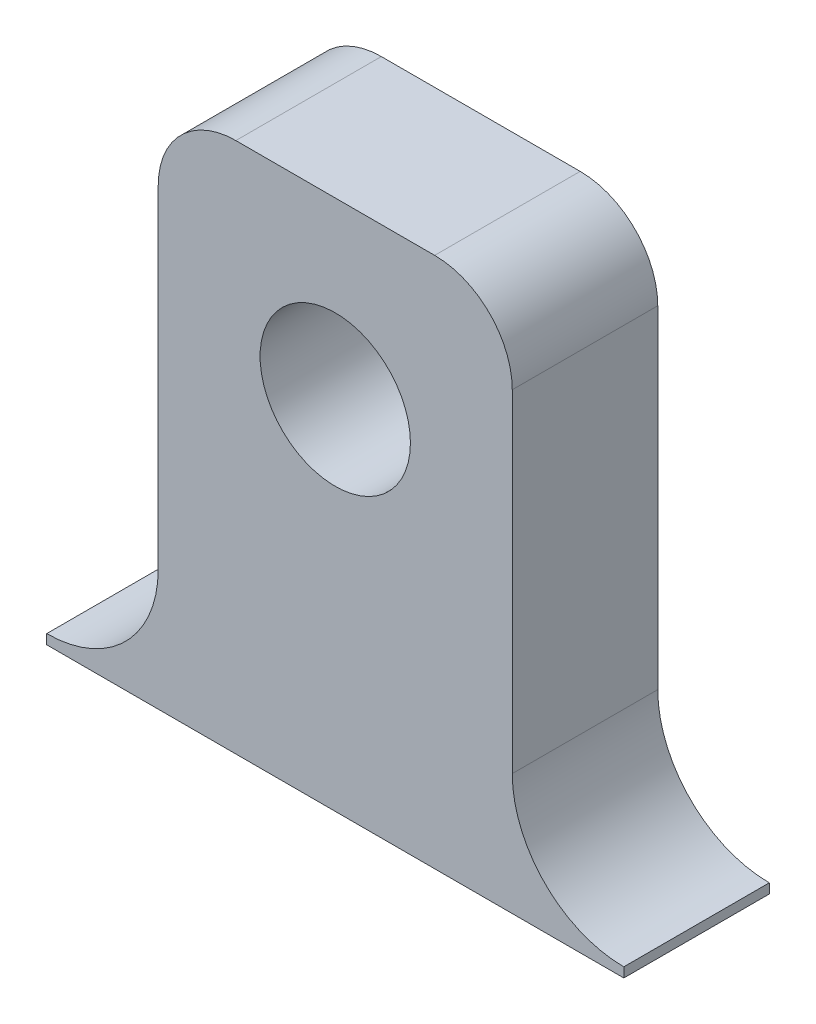
SolidWorks part; units mm, degrees
ref_plane "Front Plane" through (0, 0, 0) normal (0, 0, 1) x (1, 0, 0)
ref_plane "Top Plane" through (0, 0, 0) normal (0, 1, 0) x (1, 0, 0)
ref_plane "Right Plane" through (0, 0, 0) normal (1, 0, 0) x (0, 0, -1)
sketch "Sketch1" plane through (0, 0, 0) normal (0, 0, 1) x (1, 0, 0)
  line L4 (-5.05, 5) -> (1.55, 5) construction
  line L6 (-3.45, -2.3543) -> (3.45, -2.3543)
  line L7 (0, 9.925) -> (0, 3.45) construction
  line L9 (5.95, -2.3543) -> (-5.95, -2.3543)
  line L10 (3.65, 3) -> (3.65, 7)
  line L11 (2.05, 8.6) -> (-2.05, 8.6)
  line L12 (-3.65, 7) -> (-3.65, 3)
  line L13 (3.65, 3) -> (3.65, 0.1457)
  line L15 (-3.65, 3) -> (-3.65, 0.1457)
  line L16 (5.95, -2.1543) -> (5.95, -2.3543)
  line L17 (-5.95, -2.1543) -> (-5.95, -2.3543)
  line L18 (3.45, 5) -> (5.05, 5) construction
  circle A4 centre (0, 5) radius 1.55
  arc A7 (3.65, 7) -> (2.05, 8.6) centre (2.05, 7) ccw
  arc A8 (-2.05, 8.6) -> (-3.65, 7) centre (-2.05, 7) ccw
  arc A9 (3.65, 0.1457) -> (5.95, -2.1543) centre (5.95, 0.1457) ccw
  arc A10 (-3.65, 0.1457) -> (-5.95, -2.1543) centre (-5.95, 0.1457) cw
  point P9 (0, -2.3543)
  dimension "D2" = 3.1
extrude "Boss-Extrude1" add sketch "Sketch1" along normal blind 3
